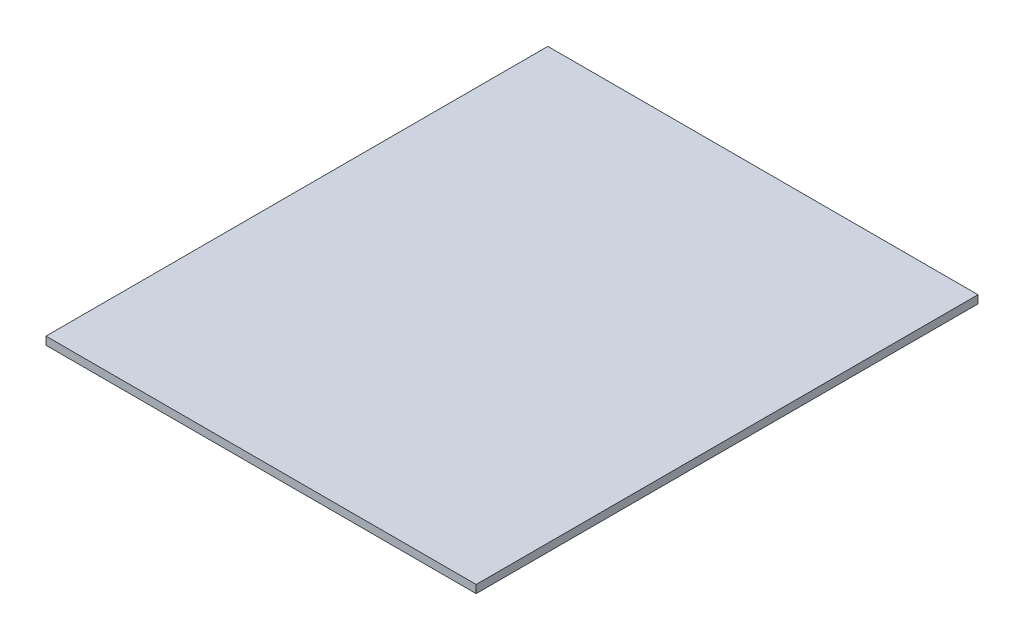
SolidWorks part; units mm, degrees
ref_plane "Front Plane" through (0, 0, 0) normal (0, 0, 1) x (1, 0, 0)
ref_plane "Top Plane" through (0, 0, 0) normal (0, 1, 0) x (1, 0, 0)
ref_plane "Right Plane" through (0, 0, 0) normal (1, 0, 0) x (0, 0, -1)
sketch "Sketch1" plane through (0, 0, 0) normal (0, 1, 0) x (1, 0, 0)
  line L1 (-270, -315) -> (270, -315)
  line L2 (-270, -315) -> (-270, 315)
  line L3 (-270, 315) -> (270, 315)
  line L4 (270, -315) -> (270, 315)
  line L5 (-270, -315) -> (270, 315) construction
  line L6 (-270, 315) -> (270, -315) construction
  point P0 (0, 0)
  dimension "D1" = 540
  dimension "D2" = 630
extrude "Boss-Extrude1" add sketch "Sketch1" along normal blind 10
